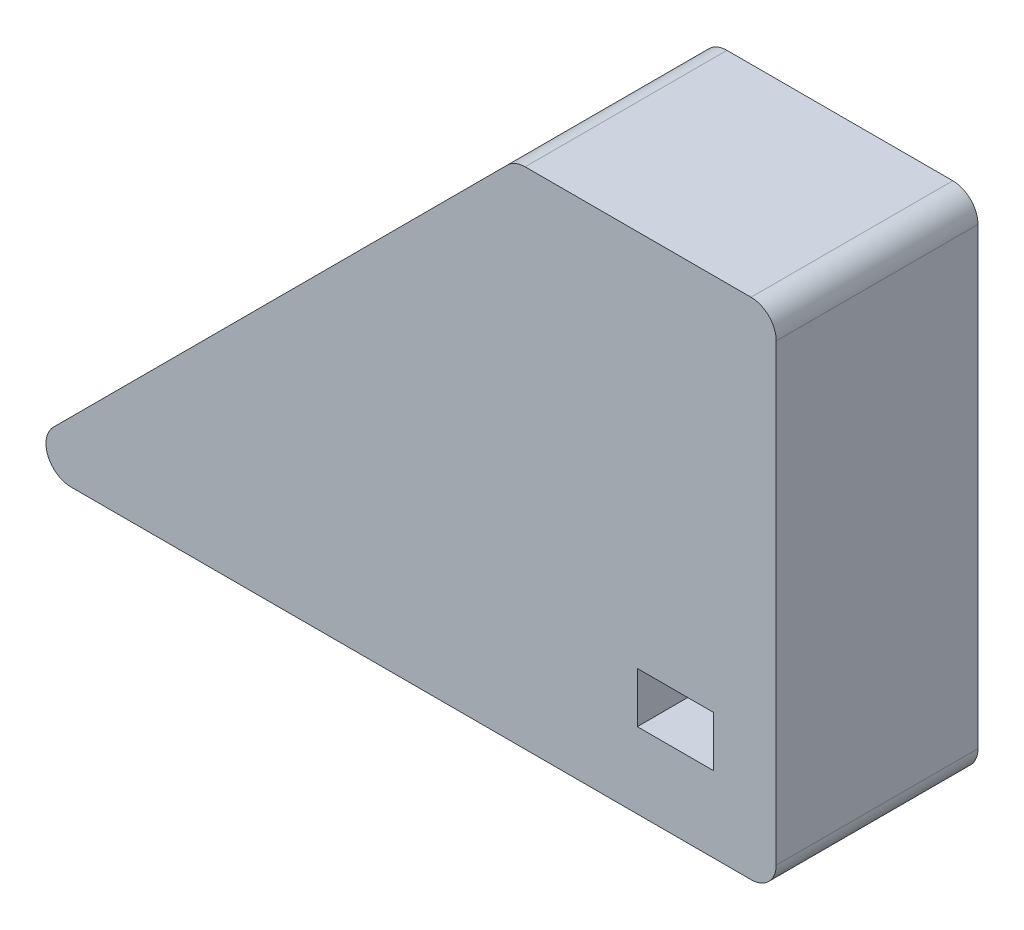
SolidWorks part; units mm, degrees
material "PET"
ref_plane "Front Plane" through (0, 0, 0) normal (0, 0, 1) x (1, 0, 0)
ref_plane "Top Plane" through (0, 0, 0) normal (0, 1, 0) x (1, 0, 0)
ref_plane "Right Plane" through (0, 0, 0) normal (1, 0, 0) x (0, 0, -1)
sketch "Sketch1" plane through (0, 0, 0) normal (0, 0, 1) x (1, 0, 0)
  line L0 (0, 0) -> (63.5, 63.5)
  line L2 (96.4235, 0) -> (0, 0)
  line L3 (96.4235, 63.5) -> (96.4235, 0)
  line L4 (63.5, 63.5) -> (96.4235, 63.5)
  dimension "D1" = 96.4235
  dimension "D2" = 45
  dimension "D3" = 63.5
extrude "Boss-Extrude1" add sketch "Sketch1" against normal blind 25.4
sketch "Sketch3" plane through (0, 0, 0) normal (0, -1, 0) x (1, 0, 0)
  line L0 (0, 0) -> (96.4235, 0) construction
  line L1 (96.4235, -25.4) -> (96.4235, 0) construction
  line L2 (0, -25.4) -> (0, 0) construction
  circle A0 centre (83.7235, -12.7) radius 2.4892
  circle A1 centre (13.8735, -12.7) radius 2.4892
  point P8 (0, 0)
  dimension "D1" = 12.7
  dimension "D3" = 4.9784
  dimension "D2" = 12.7
  dimension "D4" = 13.8735
extrude "Cut-Extrude1" cut sketch "Sketch3" against normal blind 25.4
sketch "Sketch5" plane through (0, 0, 0) normal (0, 0, 1) x (1, 0, 0)
  line L5 (96.4235, 0) -> (96.4235, 63.5) construction
  line L7 (78.9356, 15.875) -> (88.5114, 15.875)
  line L8 (78.9356, 15.875) -> (78.9356, 9.525)
  line L9 (78.9356, 9.525) -> (88.5114, 9.525)
  line L10 (88.5114, 15.875) -> (88.5114, 9.525)
  line L11 (78.9356, 15.875) -> (88.5114, 9.525) construction
  line L12 (78.9356, 9.525) -> (88.5114, 15.875) construction
  line L13 (0, 0) -> (96.4235, 0) construction
  point P6 (83.7235, 12.7)
  point P14 (12.7451, 5.4559)
  dimension "D1" = 12.7
  dimension "D2" = 12.7
  dimension "D3" = 9.5758
  dimension "D4" = 6.35
extrude "Cut-Extrude2" cut sketch "Sketch5" against normal blind 17.5133
sketch "Sketch7" plane through (0, 63.5, 0) normal (0, 1, 0) x (1, 0, 0)
  circle A0 centre (13.8735, 12.7) radius 4.7879
  dimension "D1" = 9.5758
extrude "Cut-Extrude3" cut sketch "Sketch7" against normal blind 54.61
fillet "Fillet3" radius 3.175 4 edges at (96.4235, 63.5, -12.7) (96.4235, 0, -12.7) (0, 0, -12.7) (63.5, 63.5, -12.7)
